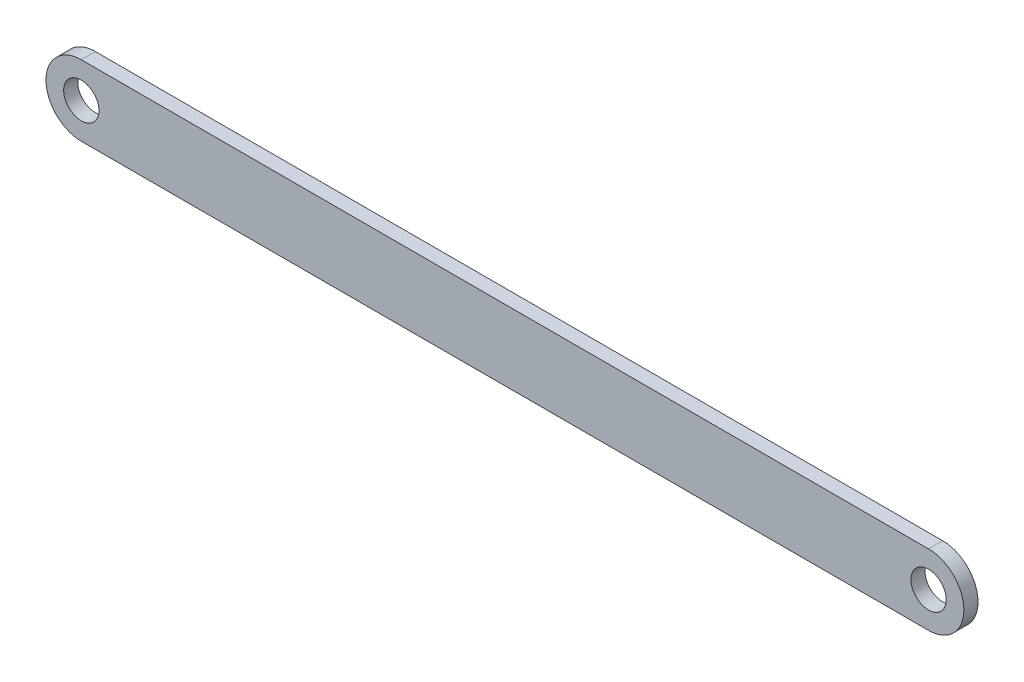
SolidWorks part; units mm, degrees
ref_plane "Front Plane" through (0, 0, 0) normal (0, 0, 1) x (1, 0, 0)
ref_plane "Top Plane" through (0, 0, 0) normal (0, 1, 0) x (1, 0, 0)
ref_plane "Right Plane" through (0, 0, 0) normal (1, 0, 0) x (0, 0, -1)
sketch "Sketch1" plane through (0, 0, 0) normal (0, 0, 1) x (1, 0, 0)
  line L1 (-76.2, 6.35) -> (76.2, 6.35)
  line L2 (-76.2, 6.35) -> (-76.2, -6.35) construction
  line L3 (-76.2, -6.35) -> (76.2, -6.35)
  line L4 (76.2, 6.35) -> (76.2, -6.35) construction
  line L5 (-76.2, 6.35) -> (76.2, -6.35) construction
  line L6 (-76.2, -6.35) -> (76.2, 6.35) construction
  arc A0 (-76.2, 6.35) -> (-76.2, -6.35) centre (-76.2, 0) ccw
  arc A1 (76.2, -6.35) -> (76.2, 6.35) centre (76.2, 0) ccw
  circle A2 centre (76.2, 0) radius 3.175
  circle A3 centre (-76.2, 0) radius 3.175
  point P0 (0, 0)
  dimension "D2" = 12.7
  dimension "D3" = 6.35
  dimension "D4" = 6.35
  dimension "D1" = 152.4
extrude "Boss-Extrude1" add sketch "Sketch1" along normal blind 2.54
